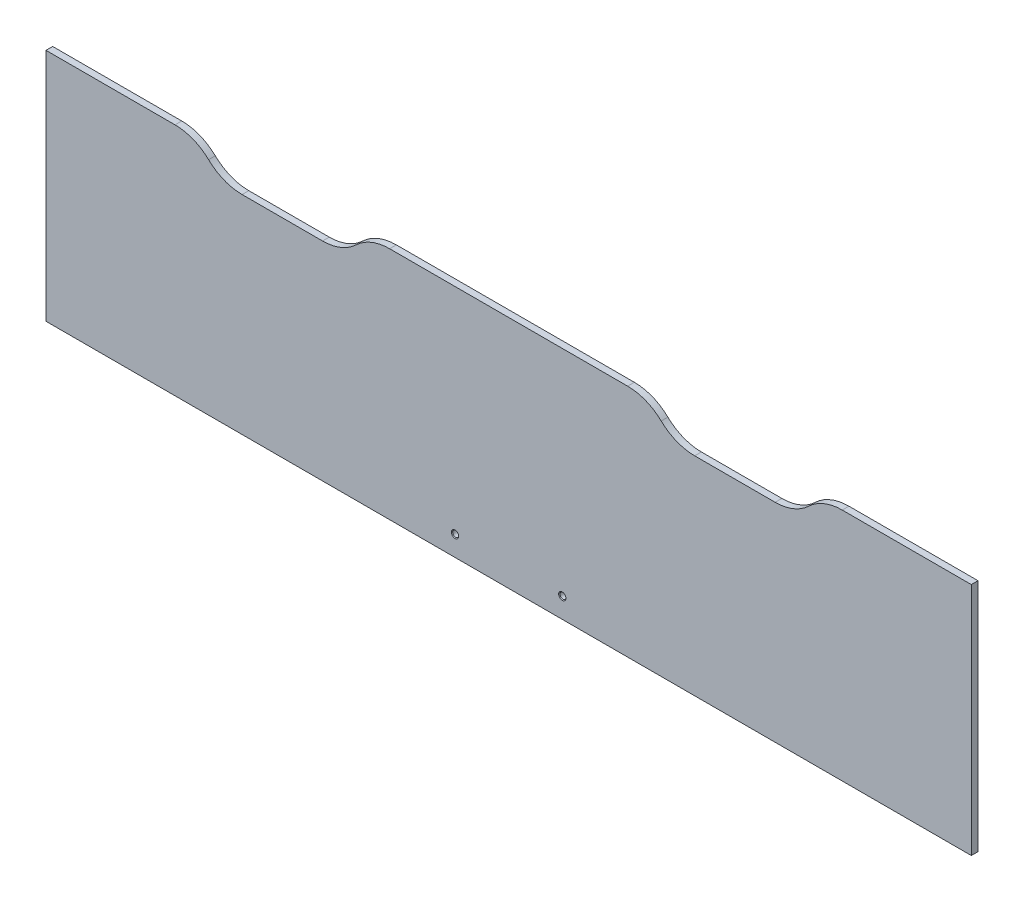
SolidWorks part; units mm, degrees
material "Beech"
ref_plane "Front Plane" through (0, 0, 0) normal (0, 0, 1) x (1, 0, 0)
ref_plane "Top Plane" through (0, 0, 0) normal (0, 1, 0) x (1, 0, 0)
ref_plane "Right Plane" through (0, 0, 0) normal (1, 0, 0) x (0, 0, -1)
sketch "Sketch1" plane through (0, 0, 0) normal (0, 0, 1) x (1, 0, 0)
  line L1 (-438.15, 0) -> (438.15, 0)
  line L2 (-438.15, 0) -> (-438.15, 222.25)
  line L3 (-438.15, 222.25) -> (438.15, 222.25)
  line L4 (438.15, 0) -> (438.15, 222.25)
  dimension "D1" = 222.25
  dimension "D3" = 876.3
extrude "Boss-Extrude1" add sketch "Sketch1" along normal blind 6.35
hole_wizard "#10 Clearance Hole1" positions "Sketch2" profile "Sketch3" hole size "#10" standard "ANSI Inch" end condition through all
sketch "Sketch2" plane through (0, 0, 6.35) normal (0, 0, 1) x (1, 0, 0)
  line L0 (-50.8, 19.05) -> (50.8, 19.05) construction
  line L2 (-438.15, 0) -> (438.15, 0) construction
  point P0 (-50.8, 19.05)
  point P2 (50.8, 19.05)
  point P11 (0, 0)
  point P12 (0, 19.05)
  dimension "D1" = 19.05
  dimension "D2" = 101.6
sketch "Sketch3" plane through (-50.8, 19.05, 6.35) normal (1, 0, 0) x (0, -1, 0)
  line L0 (0, 0) -> (0, 6.35)
  line L1 (0, 6.35) -> (2.8067, 6.35)
  line L2 (2.8067, 6.35) -> (2.8067, 0.635)
  line L3 (2.8067, 0.635) -> (3.4417, 0)
  line L5 (3.4417, 0) -> (0, 0)
  line L6 (-2.8067, 0.635) -> (-3.4417, 0) construction
  line L11 (0, -6.35) -> (0, 107.95) construction
  dimension "Thru Hole Dia." = 5.6134
  dimension "Thru Hole Depth" = 6.35
  dimension "Near C'Sink Dia." = 6.8834
  dimension "Near C'Sink Angle" = 90
sketch "Sketch4" plane through (0, 0, 0) normal (0, 0, 1) x (1, 0, 0)
  line L0 (438.15, 222.25) -> (-438.15, 222.25) construction
  line L1 (-438.15, 222.25) -> (-419.1, 222.25)
  line L2 (-438.15, 222.25) -> (-438.15, 0)
  line L3 (-438.15, 0) -> (-419.1, 0)
  line L4 (-419.1, 222.25) -> (-419.1, 0)
  line L5 (-9.525, 222.25) -> (9.525, 222.25)
  line L6 (-9.525, 222.25) -> (-9.525, 0)
  line L7 (-9.525, 0) -> (9.525, 0)
  line L8 (9.525, 222.25) -> (9.525, 0)
  line L9 (438.15, 222.25) -> (419.1, 222.25)
  line L10 (438.15, 222.25) -> (438.15, 0)
  line L11 (438.15, 0) -> (419.1, 0)
  line L12 (419.1, 222.25) -> (419.1, 0)
  line L13 (-438.15, 0) -> (438.15, 0) construction
  line L14 (-438.15, 222.25) -> (-438.15, 0) construction
  line L15 (438.15, 0) -> (438.15, 222.25) construction
  point P20 (0, 0)
  dimension "D1" = 19.05
sketch "Sketch5" plane through (0, 0, 6.35) normal (0, 0, 1) x (1, 0, 0)
  line L0 (438.15, 222.25) -> (-438.15, 222.25) construction
  line L1 (112.7125, 234.95) -> (315.9125, 234.95)
  line L2 (112.7125, 234.95) -> (112.7125, 222.25)
  line L4 (315.9125, 234.95) -> (315.9125, 222.25)
  line L5 (252.4125, 196.85) -> (176.2125, 196.85)
  line L6 (9.525, 222.25) -> (419.1, 222.25) construction
  arc A0 (315.9125, 222.25) -> (284.1625, 209.55) centre (315.9125, 176.2125) ccw
  arc A1 (284.1625, 209.55) -> (252.4125, 196.85) centre (252.4125, 242.8875) cw
  arc A2 (176.2125, 196.85) -> (144.4625, 209.55) centre (176.2125, 242.8875) cw
  arc A3 (144.4625, 209.55) -> (112.7125, 222.25) centre (112.7125, 176.2125) ccw
  point P14 (214.3125, 222.25)
  point P15 (214.3125, 196.85)
  point P16 (284.8238, 165.1)
  point P21 (214.3125, 234.95)
  dimension "D1" = 203.2
  dimension "D2" = 76.2
  dimension "D3" = 25.4
  dimension "D4" = 12.7
extrude "Cut-Extrude1" cut sketch "Sketch5" against normal through all
mirror "Mirror1" about plane through (0, 0, 0) normal (1, 0, 0) of "Cut-Extrude1"
